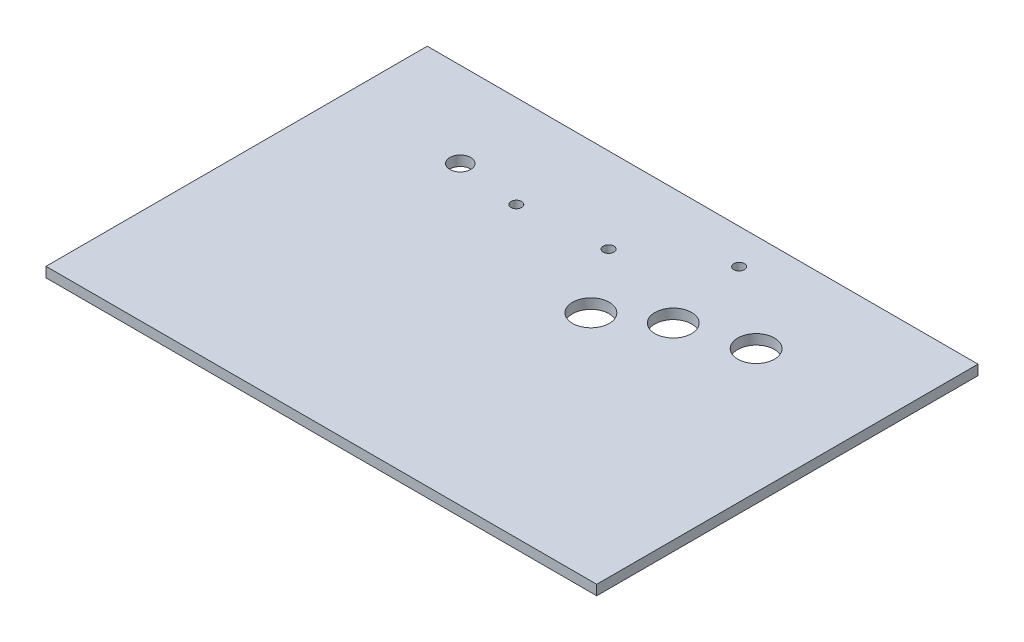
SolidWorks part; units mm, degrees
material "Mahogany"
ref_plane "Front Plane" through (0, 0, 0) normal (0, 0, 1) x (1, 0, 0)
ref_plane "Top Plane" through (0, 0, 0) normal (0, 1, 0) x (1, 0, 0)
ref_plane "Right Plane" through (0, 0, 0) normal (1, 0, 0) x (0, 0, -1)
sketch "Sketch1" plane through (0, 0, 0) normal (0, 1, 0) x (1, 0, 0)
  line L1 (0, 0) -> (330.2, 0)
  line L2 (0, 0) -> (0, 228.6)
  line L3 (0, 228.6) -> (330.2, 228.6)
  line L4 (330.2, 0) -> (330.2, 228.6)
  dimension "D1" = 228.6
  dimension "D2" = 330.2
extrude "Boss-Extrude1" add sketch "Sketch1" along normal blind 6
sketch "Sketch2" plane through (0, 6, 0) normal (0, 1, 0) x (1, 0, 0)
  line L0 (0, 228.6) -> (0, 0) construction
  line L1 (330.2, 228.6) -> (0, 228.6) construction
  line L2 (330.2, 0) -> (330.2, 228.6) construction
  circle A0 centre (70.8, 177.6) radius 6.25
  circle A1 centre (108.9, 173.1) radius 3.175
  circle A2 centre (159.7, 177.6) radius 3.175
  circle A3 centre (207.96, 207.6) radius 3.175
  circle A4 centre (187.5, 139.2) radius 11
  circle A5 centre (217.5, 158.6) radius 11
  circle A6 centre (255.6, 170.18) radius 11
  dimension "D3" = 12.5
  dimension "D4" = 6.35
  dimension "D8" = 50.8
  dimension "D9" = 21
  dimension "D10" = 99.06
  dimension "D11" = 89.4
  dimension "D13" = 30
  dimension "D14" = 22
  dimension "D1" = 70.8
  dimension "D2" = 51
  dimension "D5" = 55.5
  dimension "D6" = 108.9
  dimension "D7" = 51
  dimension "D12" = 142.7
  dimension "D15" = 70
  dimension "D16" = 38.1
  dimension "D17" = 58.42
extrude "Cut-Extrude1" cut sketch "Sketch2" against normal through all
